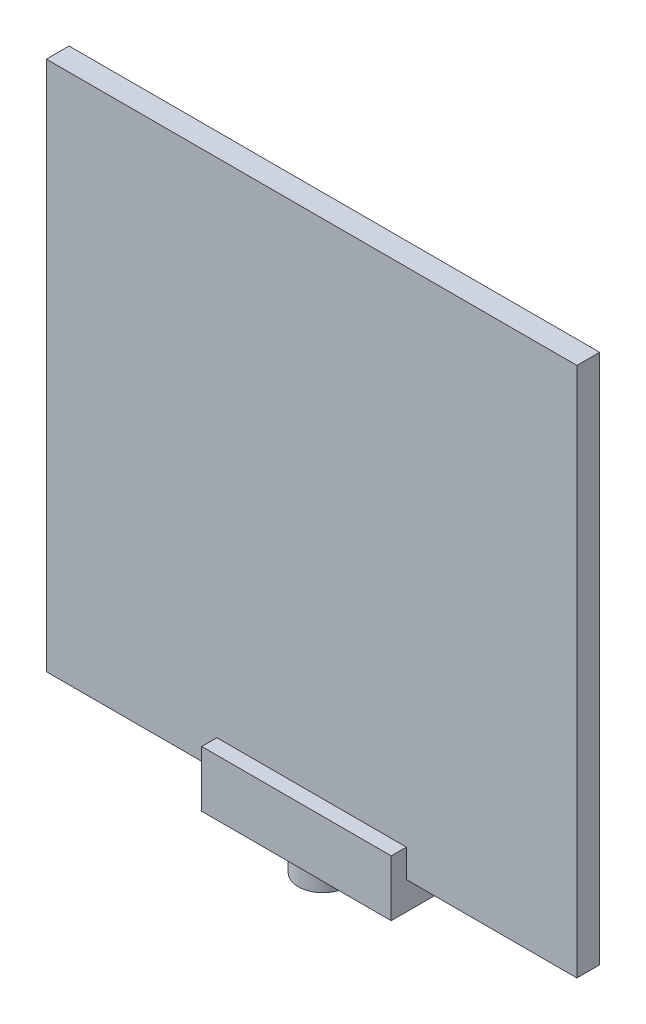
SolidWorks part; units mm, degrees
ref_plane "Front Plane" through (0, 0, 0) normal (0, 0, 1) x (1, 0, 0)
ref_plane "Top Plane" through (0, 0, 0) normal (0, 1, 0) x (1, 0, 0)
ref_plane "Right Plane" through (0, 0, 0) normal (1, 0, 0) x (0, 0, -1)
sketch "Sketch1" plane through (0, 0, 0) normal (0, 0, 1) x (1, 0, 0)
  line L1 (-35, -35) -> (35, -35)
  line L2 (-35, -35) -> (-35, 35)
  line L3 (-35, 35) -> (35, 35)
  line L4 (35, -35) -> (35, 35)
  line L5 (-35, -35) -> (35, 35) construction
  line L6 (-35, 35) -> (35, -35) construction
  point P0 (0, 0)
  dimension "D1" = 70
  dimension "D2" = 70
extrude "Boss-Extrude1" add sketch "Sketch1" along normal blind 3 contours L2 L1 L4 L3
sketch "Sketch2" plane through (0, 0, 0) normal (0, 0, -1) x (-1, 0, 0)
  line L0 (0, 35) -> (0, -49965) construction
  line L1 (35, 35) -> (-35, 35) construction
  line L2 (35, -35) -> (-35, -35) construction
  line L3 (-12.5, -38.7064) -> (12.5, -38.7064)
  line L4 (-12.5, -38.7064) -> (-12.5, -31.2936)
  line L5 (-12.5, -31.2936) -> (12.5, -31.2936)
  line L6 (12.5, -38.7064) -> (12.5, -31.2936)
  line L7 (-12.5, -38.7064) -> (12.5, -31.2936) construction
  line L8 (-12.5, -31.2936) -> (12.5, -38.7064) construction
  point P4 (0, 35)
  point P5 (0, -35)
  dimension "D1" = 25
extrude "Boss-Extrude2" add sketch "Sketch2" along normal blind 2 and the other way blind 5
sketch "Sketch3" plane through (0, -38.7064, 0) normal (0, -1, 0) x (1, 0, 0)
  line L0 (-12.5, 1.5) -> (49987.5, 1.5) construction
  line L1 (-12.5, 5) -> (-12.5, -2) construction
  line L2 (0, 5) -> (0, -49995) construction
  line L3 (12.5, 5) -> (-12.5, 5) construction
  circle A0 centre (0, 1.5) radius 2.25
  point P4 (-12.5, 1.5)
  point P9 (0, 5)
extrude "Cut-Extrude1" cut sketch "Sketch3" against normal blind 2.5
sketch "Sketch4" plane through (0, -38.7064, 0) normal (0, -1, 0) x (1, 0, 0)
  line L0 (-12.5, 1.5) -> (-11.4435, 1.5) construction
  line L1 (-12.5, 0) -> (-12.5, 3) construction
  circle A0 centre (0, 1.5) radius 3.25
  circle A1 centre (0, 1.5) radius 2.25
extrude "Boss-Extrude3" add sketch "Sketch4" along normal blind 2.5
